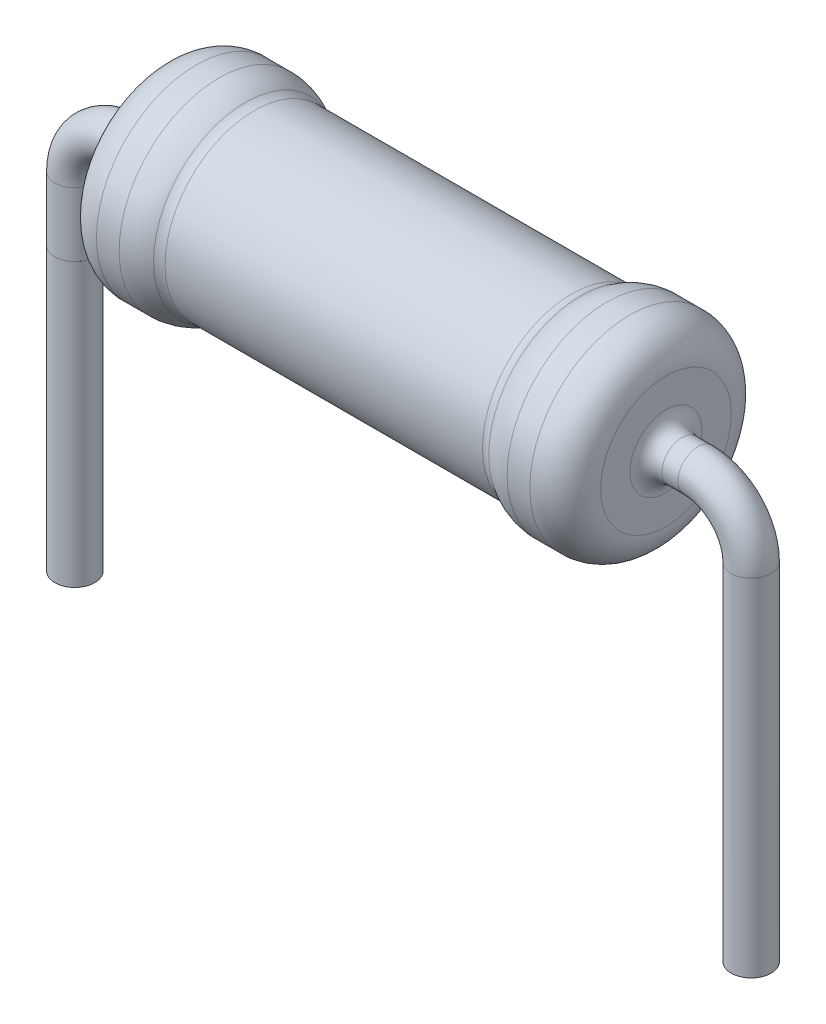
SolidWorks part; units mm, degrees
ref_plane "Front Plane" through (0, 0, 0) normal (0, 0, 1) x (1, 0, 0)
ref_plane "Top Plane" through (0, 0, 0) normal (0, 1, 0) x (1, 0, 0)
ref_plane "Right Plane" through (0, 0, 0) normal (1, 0, 0) x (0, 0, -1)
sketch "Sketch1" plane through (0, 0, 0) normal (0, 1, 0) x (1, 0, 0)
  line L0 (6.35, 0) -> (-6.35, 0) construction
  line L1 (0, 0) -> (0, 12.1522) construction
  circle A0 centre (-6.35, 0) radius 0.375
  circle A1 centre (6.35, 0) radius 0.375
  dimension "D2" = 0.75
  dimension "D1" = 6.35
extrude "Boss-Extrude1" add sketch "Sketch1" along normal blind 5.3
sketch "Sketch2" plane through (0, 0, 0) normal (0, 0, 1) x (1, 0, 0)
  line L0 (-4.75, 7.5) -> (4.75, 7.5)
  line L1 (0, 0) -> (0, 7.5) construction
  line L2 (-4.75, 7.5) -> (-4.75, 8.7258)
  line L3 (4.75, 8.7258) -> (4.75, 7.5)
  line L4 (3.643, 9.375) -> (4.0685, 9.375)
  line L5 (-2.9804, 9.175) -> (2.9804, 9.175)
  line L6 (-4.0685, 9.375) -> (-3.643, 9.375)
  arc A0 (-4.75, 8.7258) -> (-4.0685, 9.375) centre (-4.1, 8.7258) cw
  arc A1 (-3.643, 9.375) -> (-3.1464, 9.2251) centre (-3.643, 8.4773) cw
  arc A2 (-2.9804, 9.175) -> (-3.1464, 9.2251) centre (-2.9804, 9.475) cw
  arc A3 (2.9804, 9.175) -> (3.1464, 9.2251) centre (2.9804, 9.475) ccw
  arc A4 (3.643, 9.375) -> (3.1464, 9.2251) centre (3.643, 8.4773) ccw
  arc A5 (4.75, 8.7258) -> (4.0685, 9.375) centre (4.1, 8.7258) ccw
  point P6 (0, 9.375)
  point P8 (-4.75, 9.375)
  point P10 (0, 10.5)
  point P11 (-4.572, 10.5)
  point P14 (0.428, 7.5)
  point P17 (0.428, 11)
  dimension "D4" = 0.65
  dimension "D1" = 0.3
revolve "Revolve1" add sketch "Sketch2" angle 360 about L0
sketch "Sketch3" plane through (0, 0, 0) normal (0, 0, 1) x (1, 0, 0)
  line L0 (3.5, 7.5) -> (-3.5, 7.5) construction
  line L1 (5.975, 0) -> (6.725, 0) construction
  line L3 (0, 7.5) -> (0, 4.5) construction
  line L5 (3.5, 7.5) -> (5.35, 7.5)
  line L6 (6.35, 6.5) -> (6.35, 5.3)
  line L7 (6.725, 5.3) -> (5.975, 5.3) construction
  arc A0 (6.35, 6.5) -> (5.35, 7.5) centre (5.35, 6.5) ccw
  dimension "D1" = 1.2
  dimension "D3" = 1
  dimension "D2" = 7.5
sketch "Sketch4" plane through (0, 5.3, 0) normal (0, 1, 0) x (1, 0, 0)
  circle A2 centre (6.35, 0) radius 0.375
  dimension "D1" = 0.75
sweep "Sweep1" add profiles "Sketch4" path "Sketch3"
mirror "Mirror1" about plane through (0, 0, 0) normal (1, 0, 0) of "Sweep1"
fillet "Fillet2" radius 0.3 2 edges at (4.75, 7.5, -0.375) (-4.75, 7.5, 0.375)
